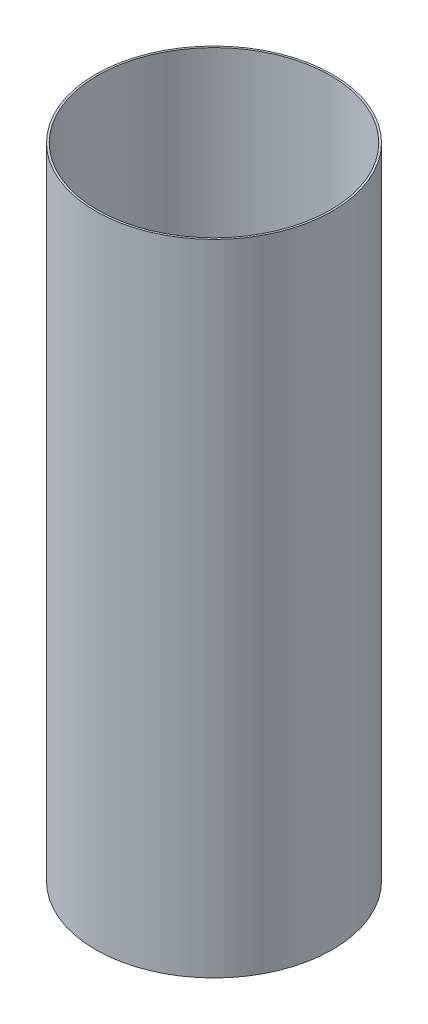
SolidWorks part; units mm, degrees
ref_plane "Front Plane" through (0, 0, 0) normal (0, 0, 1) x (1, 0, 0)
ref_plane "Top Plane" through (0, 0, 0) normal (0, 1, 0) x (1, 0, 0)
ref_plane "Right Plane" through (0, 0, 0) normal (1, 0, 0) x (0, 0, -1)
sketch "Sketch1" plane through (0, 0, 0) normal (0, 1, 0) x (1, 0, 0)
  circle A0 centre (0, 0) radius 24.23
  circle A1 centre (0, 0) radius 24.63
  dimension "D1" = 48.46
  dimension "D2" = 0.4
extrude "Boss-Extrude1" add sketch "Sketch1" along normal blind 133
equation "\"D1@Sketch1\"=1.9in+0.2mm"
